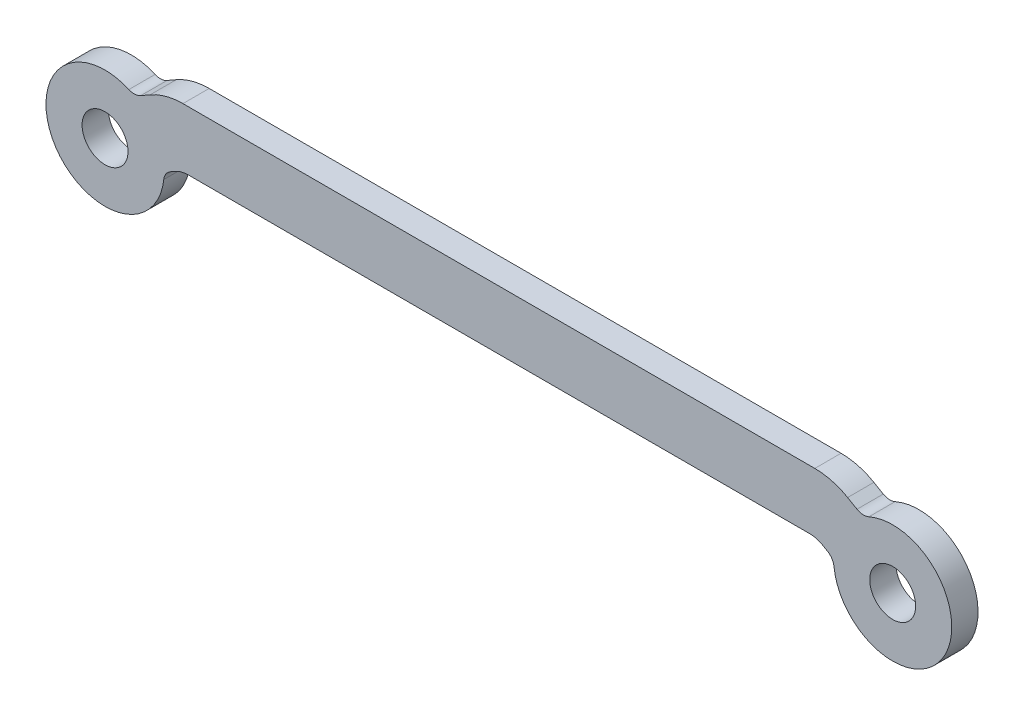
SolidWorks part; units mm, degrees
ref_plane "Front Plane" through (0, 0, 0) normal (0, 0, 1) x (1, 0, 0)
ref_plane "Top Plane" through (0, 0, 0) normal (0, 1, 0) x (1, 0, 0)
ref_plane "Right Plane" through (0, 0, 0) normal (1, 0, 0) x (0, 0, -1)
sketch "Sketch1" plane through (0, 0, 0) normal (0, 0, 1) x (1, 0, 0)
  line L7 (2.7176, 4.1671) -> (3.433, 4.5801)
  line L8 (5.933, 5.25) -> (54.067, 5.25)
  line L9 (56.567, 4.5801) -> (57.2824, 4.1671)
  line L10 (0, 0) -> (60, 0) construction
  line L11 (55.0324, 0.27) -> (54.6651, 0.4821)
  line L12 (53.6651, 0.75) -> (6.351, 0.75)
  line L13 (5.3211, 0.474) -> (4.9676, 0.27)
  line L14 (4.5933, 5.25) -> (5.799, 0.75) construction
  line L15 (0, 0) -> (5.1962, 3) construction
  line L16 (55.4067, 5.25) -> (54.201, 0.75) construction
  line L17 (60, 0) -> (54.8038, 3) construction
  arc A0 (56.567, 4.5801) -> (54.067, 5.25) centre (54.067, 0.25) ccw
  arc A1 (5.933, 5.25) -> (3.433, 4.5801) centre (5.933, 0.25) ccw
  circle A8 centre (0, 0) radius 1.75
  arc A9 (1.8144, 4.118) -> (4.4735, -0.4877) centre (0, 0) ccw
  circle A10 centre (60, 0) radius 1.75
  arc A11 (55.5265, -0.4877) -> (58.1856, 4.118) centre (60, 0) ccw
  arc A12 (55.0324, 0.27) -> (55.5265, -0.4877) centre (54.5324, -0.5961) cw
  arc A13 (57.2824, 4.1671) -> (58.1856, 4.118) centre (57.7824, 5.0331) ccw
  arc A14 (2.7176, 4.1671) -> (1.8144, 4.118) centre (2.2176, 5.0331) cw
  arc A15 (4.9676, 0.27) -> (4.4735, -0.4877) centre (5.4676, -0.5961) ccw
  arc A16 (54.6651, 0.4821) -> (53.6651, 0.75) centre (53.6651, -1.25) ccw
  arc A18 (6.351, 0.75) -> (5.3211, 0.474) centre (6.351, -1.3098) ccw
  dimension "D2" = 5
  dimension "D7" = 3.5
  dimension "D8" = 9
  dimension "D9" = 9
  dimension "D10" = 3.5
  dimension "D18" = 1
  dimension "D19" = 2
  dimension "D11" = 4.5
  dimension "D12" = 0.75
  dimension "D13" = 4.5
  dimension "D14" = 60
  dimension "D15" = 4.5
  dimension "D16" = 30
  dimension "D17" = 30
extrude "Boss-Extrude1" add sketch "Sketch1" along normal blind 2
